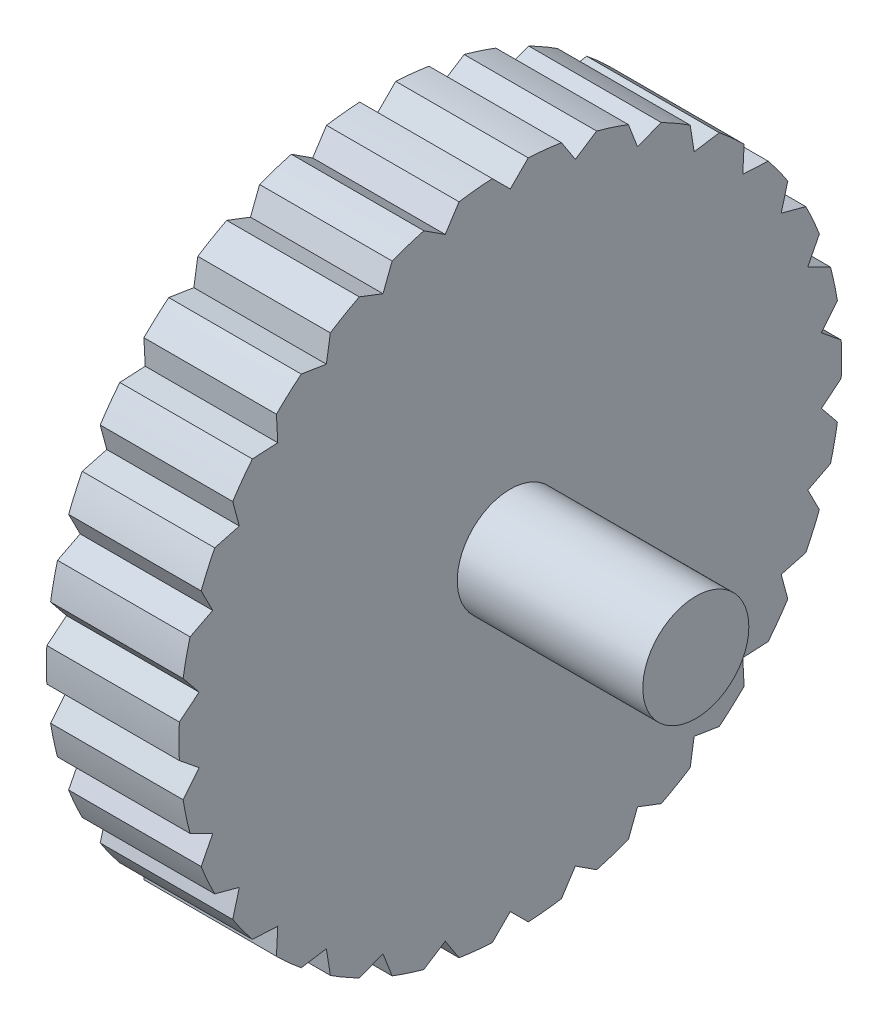
SolidWorks part; units mm, degrees
ref_plane "Front Plane" through (0, 0, 0) normal (0, 0, 1) x (1, 0, 0)
ref_plane "Top Plane" through (0, 0, 0) normal (0, 1, 0) x (1, 0, 0)
ref_plane "Right Plane" through (0, 0, 0) normal (1, 0, 0) x (0, 0, -1)
sketch "Sketch1" plane through (0, 0, 0) normal (1, 0, 0) x (0, 0, -1)
  circle A0 centre (0, 0) radius 5.08
  dimension "D1" = 10.16
extrude "Boss-Extrude1" add sketch "Sketch1" along normal blind 17.78
sketch "Sketch2" plane through (0, 0, 0) normal (-1, 0, 0) x (0, 0, 1)
  circle A0 centre (0, 0) radius 31.75
  dimension "D1" = 63.5
extrude "Boss-Extrude2" add sketch "Sketch2" along normal blind 12.7
sketch "Sketch3" plane through (-12.7, 0, 0) normal (-1, 0, 0) x (0, 0, 1)
  line L0 (-2.63, 31.6409) -> (0, 33.6867)
  line L1 (0, 33.6867) -> (3.0837, 31.5999)
  circle A1 centre (0, 0) radius 31.75 construction
  arc A2 (3.0837, 31.5999) -> (-2.63, 31.6409) centre (0, 0) ccw
extrude "Cut-Extrude1" [suppressed] cut sketch "Sketch3" against normal through all both and the other way through all
pattern_circular "CirPattern1" [suppressed] count 22 over 360
sketch "Sketch5" plane through (0, 0, 0) normal (1, 0, 0) x (0, 0, -1)
  line L0 (0, 32.888) -> (0, 6.1765) construction
  line L1 (0, 29.9801) -> (1.7231, 31.7032)
  line L2 (0, 29.9801) -> (-1.7231, 31.7032)
  circle A0 centre (0, 0) radius 31.75 construction
  arc A1 (1.7231, 31.7032) -> (-1.7231, 31.7032) centre (0, 0) ccw
extrude "Cut-Extrude2" cut sketch "Sketch5" against normal through all
pattern_circular "CirPattern2" count 30 over 360 about axis through (0, 0, 0) along (1, 0, 0) of "Cut-Extrude2"
